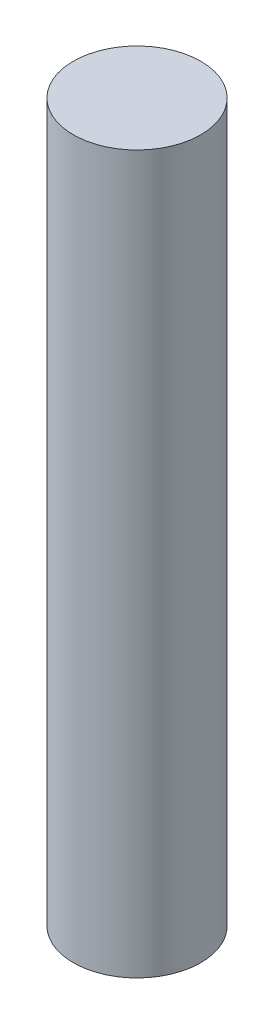
SolidWorks part; units mm, degrees
ref_plane "Front Plane" through (0, 0, 0) normal (0, 0, 1) x (1, 0, 0)
ref_plane "Top Plane" through (0, 0, 0) normal (0, 1, 0) x (1, 0, 0)
ref_plane "Right Plane" through (0, 0, 0) normal (1, 0, 0) x (0, 0, -1)
other "Configuration Table"
sketch "Sketch1" plane through (0, 0, 0) normal (0, 1, 0) x (1, 0, 0)
  circle A0 centre (350, 300) radius 8
extrude "OVEN_kesme_aktuator_mili" add sketch "Sketch1" along normal blind 90 from offset 470 separate body
